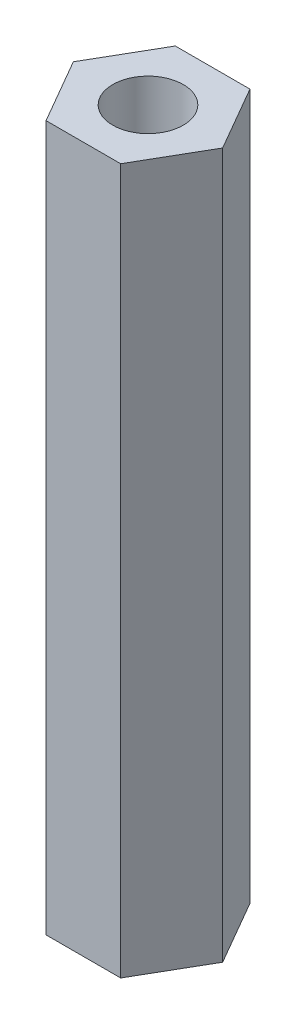
SolidWorks part; units mm, degrees
material "黄铜"
ref_plane "前视基准面" through (0, 0, 0) normal (0, 0, 1) x (1, 0, 0)
ref_plane "上视基准面" through (0, 0, 0) normal (0, 1, 0) x (1, 0, 0)
ref_plane "右视基准面" through (0, 0, 0) normal (1, 0, 0) x (0, 0, -1)
other "Configuration Table"
sketch "草图1" plane through (0, 0, 0) normal (0, 1, 0) x (1, 0, 0)
  line L1 (3.1754, 0) -> (1.5877, 2.75)
  line L2 (1.5877, 2.75) -> (-1.5877, 2.75)
  line L3 (-1.5877, 2.75) -> (-3.1754, 0)
  line L4 (-3.1754, 0) -> (-1.5877, -2.75)
  line L5 (-1.5877, -2.75) -> (1.5877, -2.75)
  line L6 (1.5877, -2.75) -> (3.1754, 0)
  circle A0 centre (0, 0) radius 2.75 construction
  circle A1 centre (0, 0) radius 1.5
  dimension "D1" = 5.5
  dimension "D2" = 3
extrude "凸台-拉伸1" add sketch "草图1" along normal blind 30
